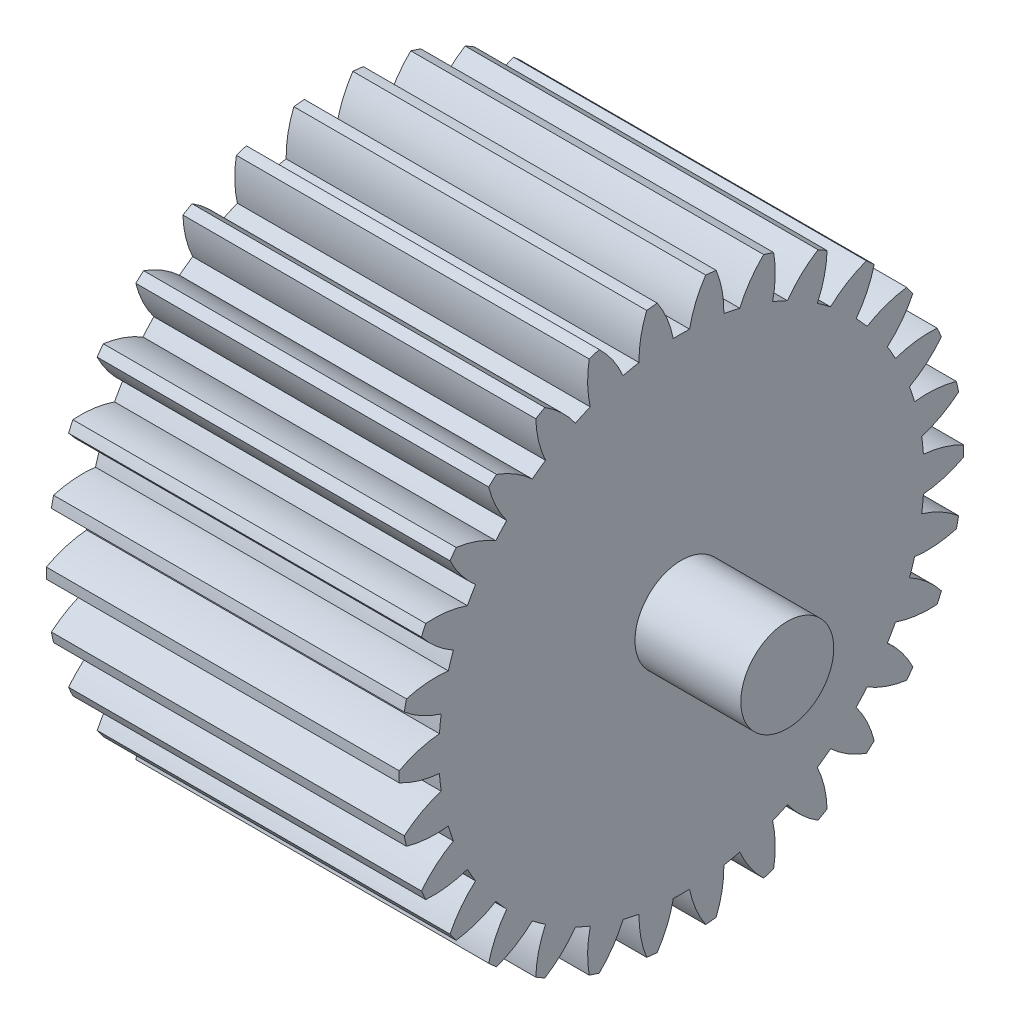
SolidWorks part; units mm, degrees
ref_plane "Plane1" through (0, 0, 0) normal (0, 0, 1) x (1, 0, 0)
ref_plane "Plane2" through (0, 0, 0) normal (0, 1, 0) x (1, 0, 0)
ref_plane "Plane3" through (0, 0, 0) normal (1, 0, 0) x (0, 0, -1)
sketch "HoldingSke" plane through (0, 0, 0) normal (0, 1, 0) x (1, 0, 0)
  line L0 (0, 0) -> (0.5774, -0.3333)
  line L1 (-15, 0) -> (100, 0) construction
  line L2 (0, 0) -> (-2.1039, 2.3779)
  line L3 (0, 0) -> (-11.863, 4.5341)
  line L4 (0, 0) -> (7.479, 4.318)
  line L5 (0, 0) -> (-37.4781, -13.9782)
  line L6 (0, 0) -> (-16.5793, -11.1861)
  line L7 (-2.1039, 2.3779) -> (6.5061, 41.4403)
  line L8 (-76.2, 54.61) -> (-74.8, 54.61)
  line L9 (-71.009, 38.7566) -> (-53.1078, 45.2721)
  line L10 (-76.2, 71.12) -> (104.1128, 71.12)
  line L11 (0, 0) -> (-20, 0)
  line L12 (-76.2, 101.6) -> (-76.147, 101.6)
  line L13 (24.9733, 27.94) -> (52.9518, 28.4284)
  line L14 (24.9733, 27.94) -> (24.9743, 27.94)
  line L15 (24.9733, 27.94) -> (100.4006, 29.5858)
  line L16 (-63.627, -1.5) -> (-12.827, -1.5)
  circle A0 centre (0, 0) radius 4
  circle A1 centre (0, 0) radius 10
  circle A2 centre (0, 0) radius 10
  circle A3 centre (0, 0) radius 4
  dimension "MHD" = 20
  dimension "Hub_dia" = 20
  dimension "Bore" = 8
  dimension "MBD" = 8
  dimension "Num_teeth" = 30
  dimension "Pitch" = 0.6667
  dimension "Overall_len" = 40
  dimension "Show_teeth" = 30
  dimension "Thickness" = 20
  dimension "OAL" = 40.0001
  dimension "T_dim" = 1.4
  dimension "Ap" = 20
  dimension "H" = 19.05
  dimension "Pitch_radius" = 180.3128
  dimension "Width" = 20
  dimension "Backlash" = 0.053
  dimension "Addendum_fac" = 1
  dimension "Dedendum_fac" = 1.25
  dimension "Clearance_fac" = 0.25
  dimension "Dedendum_add" = 0.001
  dimension "Module" = 1.5
sketch "BasProSke" plane through (0, 0, 0) normal (0, 1, 0) x (1, 0, 0)
  line L0 (-10, 0) -> (60, 0) construction
  line L1 (0, 0) -> (0, 24)
  line L2 (0, 0) -> (20, 0)
  line L3 (20, 0) -> (20, 24)
  line L4 (20, 24) -> (0, 24)
  dimension "Thickness" = 20
  dimension "Diameter" = 48
revolve "Base-Revolve" add sketch "BasProSke" angle 360 about L0
sketch "TooCutSke" plane through (0, 0, 0) normal (1, 0, 0) x (0, 0, -1)
  line L1 (0, 0) -> (0, 107) construction
  line L2 (0, 0) -> (-1.2703, 22.4641) construction
  line L3 (0, 0) -> (-4.6983, 44.7014) construction
  line L4 (-1.2703, 22.4641) -> (-2.3492, 22.3507) construction
  arc A0 (0.6933, 20.6123) -> (-0.6933, 20.6123) centre (0, 0) ccw
  arc A1 (2.0805, 23.9351) -> (-2.0805, 23.9351) centre (0, 0) ccw
  circle A2 centre (0, 0) radius 22.5 construction
  circle A3 centre (0, 0) radius 21.1431 construction
  arc A4 (-0.6933, 20.6123) -> (-2.0805, 23.9351) centre (-9.5243, 18.8764) ccw
  arc A5 (2.0805, 23.9351) -> (0.6933, 20.6123) centre (9.5243, 18.8764) ccw
  dimension "Root_dia" = 41.248
  dimension "Overcut_dia" = 48.0508
  dimension "Pitch_dia" = 45
  dimension "Base_dia" = 42.2862
  dimension "Flank_rad" = 9
  dimension "Half_ang" = 6
  dimension "Half_CT" = 1.0848
extrude "ToothCut" cut sketch "TooCutSke" along normal through all
fillet "Breaks" [suppressed] radius 0.03
fillet "RootFillets" [suppressed] radius 0.376
pattern_circular "TeethCuts" count 30 over 360 about axis through (0, 0, 0) along (1, 0, 0) of "ToothCut", "RootFillets", "Breaks"
sketch "HubNeaOneSke" plane through (0, 0, 0) normal (-1, 0, 0) x (0, 0, 1)
  circle A0 centre (0, 0) radius 10
  dimension "Diameter" = 20
extrude "HubNearOne" [suppressed] add sketch "HubNeaOneSke" along normal blind 20.0001
sketch "HubNeaBotSke" plane through (0, 0, 0) normal (-1, 0, 0) x (0, 0, 1)
  circle A0 centre (0, 0) radius 10
  dimension "Diameter" = 20
extrude "HubNearBoth" add sketch "HubNeaBotSke" along normal blind 10
ref_plane "FarPln" through (20, 0, 0) normal (1, 0, 0) x (0, 0, -1)
sketch "HubFarSke" plane through (20, 0, 0) normal (1, 0, 0) x (0, 0, -1)
  circle A0 centre (0, 0) radius 10
  dimension "Diameter" = 20
extrude "HubFar" add sketch "HubFarSke" along normal blind 10
sketch "BorSke" plane through (0, 0, 0) normal (1, 0, 0) x (0, 0, -1)
  circle A0 centre (0, 0) radius 4
  dimension "Diameter" = 8
extrude "Bore" cut sketch "BorSke" along normal mid plane 80.0001
sketch "KeySke" plane through (0, 0, 0) normal (1, 0, 0) x (0, 0, -1)
  line L0 (-1, 0) -> (-1, 5.4)
  line L1 (-1, 5.4) -> (1, 5.4)
  line L2 (1, 5.4) -> (1, 0)
  line L3 (0, 0) -> (0, 34) construction
  line L4 (-1, 0) -> (1, 0)
  dimension "Offset" = 5.4
extrude "Keyway" [suppressed] cut sketch "KeySke" along normal mid plane 80.0001
pattern_circular "Keyway2" [suppressed] count 2 every 90 about axis through (-10, 0, 0) along (1, 0, 0)
sketch "Croquis1" plane through (30, 0, 0) normal (1, 0, 0) x (0, 0, -1)
  circle A0 centre (0, 0) radius 10
extrude "Cortar-Extruir1" cut sketch "Croquis1" against normal up to surface (10 mm away) up to face at (20, 0, 10)
sketch "Croquis3" plane through (20, 0, 0) normal (1, 0, 0) x (0, 0, -1)
  circle A0 centre (0, 0) radius 4
extrude "Saliente-Extruir1" add sketch "Croquis3" against normal up to surface (30 mm away) up to face at (-10, 0, 4)
sketch "Croquis4" plane through (20, 0, 0) normal (1, 0, 0) x (0, 0, -1)
  circle A0 centre (0, 0) radius 3.95
  dimension "D1" = 7.9
extrude "Saliente-Extruir2" add sketch "Croquis4" along normal blind 9
sketch "Croquis5" plane through (-10, 0, 0) normal (-1, 0, 0) x (0, 0, 1)
  circle A0 centre (0, 0) radius 11.0881
extrude "Cortar-Extruir2" cut sketch "Croquis5" against normal up to surface (10 mm away) up to face at (0, 0, -10)
sketch "Croquis6" plane through (0, 0, 0) normal (-1, 0, 0) x (0, 0, 1)
  arc A120 (20.5719, -1.4651) -> (23.9958, -0.4465) centre (19.7685, 7.499) ccw
  arc A121 (23.9958, -0.4465) -> (23.9958, 0.4465) centre (0, 0) ccw
  arc A122 (23.9958, 0.4465) -> (20.5719, 1.4651) centre (19.7685, -7.499) ccw
  arc A123 (20.5719, 1.4651) -> (20.427, 2.8441) centre (0, 0) ccw
  arc A124 (20.427, 2.8441) -> (23.5643, 4.5523) centre (17.7774, 11.4452) ccw
  arc A125 (23.5643, 4.5523) -> (23.3787, 5.4257) centre (0, 0) ccw
  arc A126 (23.3787, 5.4257) -> (19.8177, 5.7102) centre (20.8957, -3.225) ccw
  arc A127 (19.8177, 5.7102) -> (19.3893, 7.0289) centre (0, 0) ccw
  arc A128 (19.3893, 7.0289) -> (22.1029, 9.3521) centre (15.0094, 14.8912) ccw
  arc A129 (22.1029, 9.3521) -> (21.7397, 10.1678) centre (0, 0) ccw
  arc A130 (21.7397, 10.1678) -> (18.1975, 9.7058) centre (21.1096, 1.1899) ccw
  arc A131 (18.1975, 9.7058) -> (17.5042, 10.9066) centre (0, 0) ccw
  arc A132 (17.5042, 10.9066) -> (19.6755, 13.7432) centre (11.5853, 17.6865) ccw
  arc A133 (19.6755, 13.7432) -> (19.1506, 14.4656) centre (0, 0) ccw
  arc A134 (19.1506, 14.4656) -> (15.7819, 13.2771) centre (20.4009, 5.5529) ccw
  arc A135 (15.7819, 13.2771) -> (14.8541, 14.3076) centre (0, 0) ccw
  arc A136 (14.8541, 14.3076) -> (16.3881, 17.5337) centre (7.6549, 19.7087) ccw
  arc A137 (16.3881, 17.5337) -> (15.7246, 18.1311) centre (0, 0) ccw
  arc A138 (15.7246, 18.1311) -> (12.6765, 16.2682) centre (18.8006, 9.6731) ccw
  arc A139 (12.6765, 16.2682) -> (11.5548, 17.0832) centre (0, 0) ccw
  arc A140 (11.5548, 17.0832) -> (12.3846, 20.5578) centre (3.39, 20.8696) ccw
  arc A141 (12.3846, 20.5578) -> (11.6113, 21.0042) centre (0, 0) ccw
  arc A142 (11.6113, 21.0042) -> (9.0171, 18.5483) centre (16.3786, 13.3706) ccw
  arc A143 (9.0171, 18.5483) -> (7.7505, 19.1123) centre (0, 0) ccw
  arc A144 (7.7505, 19.1123) -> (7.8397, 22.6834) centre (-1.0231, 21.1183) ccw
  arc A145 (7.8397, 22.6834) -> (6.9905, 22.9594) centre (0, 0) ccw
  arc A146 (6.9905, 22.9594) -> (4.9637, 20.0178) centre (13.2408, 16.4837) ccw
  arc A147 (4.9637, 20.0178) -> (3.6074, 20.3061) centre (0, 0) ccw
  arc A148 (3.6074, 20.3061) -> (2.9523, 23.8177) centre (-5.3915, 20.4441) ccw
  arc A149 (2.9523, 23.8177) -> (2.0642, 23.9111) centre (0, 0) ccw
  arc A150 (2.0642, 23.9111) -> (0.6933, 20.6123) centre (9.5243, 18.8764) ccw
  arc A151 (0.6933, 20.6123) -> (-0.6933, 20.6123) centre (0, 0) ccw
  arc A152 (-0.6933, 20.6123) -> (-2.0642, 23.9111) centre (-9.5243, 18.8764) ccw
  arc A153 (-2.0642, 23.9111) -> (-2.9523, 23.8177) centre (0, 0) ccw
  arc A154 (-2.9523, 23.8177) -> (-3.6074, 20.3061) centre (5.3915, 20.4441) ccw
  arc A155 (-3.6074, 20.3061) -> (-4.9637, 20.0178) centre (0, 0) ccw
  arc A156 (-4.9637, 20.0178) -> (-6.9905, 22.9594) centre (-13.2408, 16.4837) ccw
  arc A157 (-6.9905, 22.9594) -> (-7.8397, 22.6834) centre (0, 0) ccw
  arc A158 (-7.8397, 22.6834) -> (-7.7505, 19.1123) centre (1.0231, 21.1183) ccw
  arc A159 (-7.7505, 19.1123) -> (-9.0171, 18.5483) centre (0, 0) ccw
  arc A160 (-9.0171, 18.5483) -> (-11.6113, 21.0042) centre (-16.3786, 13.3706) ccw
  arc A161 (-11.6113, 21.0042) -> (-12.3846, 20.5578) centre (0, 0) ccw
  arc A162 (-12.3846, 20.5578) -> (-11.5548, 17.0832) centre (-3.39, 20.8696) ccw
  arc A163 (-11.5548, 17.0832) -> (-12.6765, 16.2682) centre (0, 0) ccw
  arc A164 (-12.6765, 16.2682) -> (-15.7246, 18.1311) centre (-18.8006, 9.6731) ccw
  arc A165 (-15.7246, 18.1311) -> (-16.3881, 17.5337) centre (0, 0) ccw
  arc A166 (-16.3881, 17.5337) -> (-14.8541, 14.3076) centre (-7.6549, 19.7087) ccw
  arc A167 (-14.8541, 14.3076) -> (-15.7819, 13.2771) centre (0, 0) ccw
  arc A168 (-15.7819, 13.2771) -> (-19.1506, 14.4656) centre (-20.4009, 5.5529) ccw
  arc A169 (-19.1506, 14.4656) -> (-19.6755, 13.7432) centre (0, 0) ccw
  arc A170 (-19.6755, 13.7432) -> (-17.5042, 10.9066) centre (-11.5853, 17.6865) ccw
  arc A171 (-17.5042, 10.9066) -> (-18.1975, 9.7058) centre (0, 0) ccw
  arc A172 (-18.1975, 9.7058) -> (-21.7397, 10.1678) centre (-21.1096, 1.1899) ccw
  arc A173 (-21.7397, 10.1678) -> (-22.1029, 9.3521) centre (0, 0) ccw
  arc A174 (-22.1029, 9.3521) -> (-19.3893, 7.0289) centre (-15.0094, 14.8912) ccw
  arc A175 (-19.3893, 7.0289) -> (-19.8177, 5.7102) centre (0, 0) ccw
  arc A176 (-19.8177, 5.7102) -> (-23.3787, 5.4257) centre (-20.8957, -3.225) ccw
  arc A177 (-23.3787, 5.4257) -> (-23.5643, 4.5523) centre (0, 0) ccw
  arc A178 (-23.5643, 4.5523) -> (-20.427, 2.8441) centre (-17.7774, 11.4452) ccw
  arc A179 (-20.427, 2.8441) -> (-20.5719, 1.4651) centre (0, 0) ccw
  arc A180 (-20.5719, 1.4651) -> (-23.9958, 0.4465) centre (-19.7685, -7.499) ccw
  arc A181 (-23.9958, 0.4465) -> (-23.9958, -0.4465) centre (0, 0) ccw
  arc A182 (-23.9958, -0.4465) -> (-20.5719, -1.4651) centre (-19.7685, 7.499) ccw
  arc A183 (-20.5719, -1.4651) -> (-20.427, -2.8441) centre (0, 0) ccw
  arc A184 (-20.427, -2.8441) -> (-23.5643, -4.5523) centre (-17.7774, -11.4452) ccw
  arc A185 (-23.5643, -4.5523) -> (-23.3787, -5.4257) centre (0, 0) ccw
  arc A186 (-23.3787, -5.4257) -> (-19.8177, -5.7102) centre (-20.8957, 3.225) ccw
  arc A187 (-19.8177, -5.7102) -> (-19.3893, -7.0289) centre (0, 0) ccw
  arc A188 (-19.3893, -7.0289) -> (-22.1029, -9.3521) centre (-15.0094, -14.8912) ccw
  arc A189 (-22.1029, -9.3521) -> (-21.7397, -10.1678) centre (0, 0) ccw
  arc A190 (-21.7397, -10.1678) -> (-18.1975, -9.7058) centre (-21.1096, -1.1899) ccw
  arc A191 (-18.1975, -9.7058) -> (-17.5042, -10.9066) centre (0, 0) ccw
  arc A192 (-17.5042, -10.9066) -> (-19.6755, -13.7432) centre (-11.5853, -17.6865) ccw
  arc A193 (-19.6755, -13.7432) -> (-19.1506, -14.4656) centre (0, 0) ccw
  arc A194 (-19.1506, -14.4656) -> (-15.7819, -13.2771) centre (-20.4009, -5.5529) ccw
  arc A195 (-15.7819, -13.2771) -> (-14.8541, -14.3076) centre (0, 0) ccw
  arc A196 (-14.8541, -14.3076) -> (-16.3881, -17.5337) centre (-7.6549, -19.7087) ccw
  arc A197 (-16.3881, -17.5337) -> (-15.7246, -18.1311) centre (0, 0) ccw
  arc A198 (-15.7246, -18.1311) -> (-12.6765, -16.2682) centre (-18.8006, -9.6731) ccw
  arc A199 (-12.6765, -16.2682) -> (-11.5548, -17.0832) centre (0, 0) ccw
  arc A200 (-11.5548, -17.0832) -> (-12.3846, -20.5578) centre (-3.39, -20.8696) ccw
  arc A201 (-12.3846, -20.5578) -> (-11.6113, -21.0042) centre (0, 0) ccw
  arc A202 (-11.6113, -21.0042) -> (-9.0171, -18.5483) centre (-16.3786, -13.3706) ccw
  arc A203 (-9.0171, -18.5483) -> (-7.7505, -19.1123) centre (0, 0) ccw
  arc A204 (-7.7505, -19.1123) -> (-7.8397, -22.6834) centre (1.0231, -21.1183) ccw
  arc A205 (-7.8397, -22.6834) -> (-6.9905, -22.9594) centre (0, 0) ccw
  arc A206 (-6.9905, -22.9594) -> (-4.9637, -20.0178) centre (-13.2408, -16.4837) ccw
  arc A207 (-4.9637, -20.0178) -> (-3.6074, -20.3061) centre (0, 0) ccw
  arc A208 (-3.6074, -20.3061) -> (-2.9523, -23.8177) centre (5.3915, -20.4441) ccw
  arc A209 (-2.9523, -23.8177) -> (-2.0642, -23.9111) centre (0, 0) ccw
  arc A210 (-2.0642, -23.9111) -> (-0.6933, -20.6123) centre (-9.5243, -18.8764) ccw
  arc A211 (-0.6933, -20.6123) -> (0.6933, -20.6123) centre (0, 0) ccw
  arc A212 (0.6933, -20.6123) -> (2.0642, -23.9111) centre (9.5243, -18.8764) ccw
  arc A213 (2.0642, -23.9111) -> (2.9523, -23.8177) centre (0, 0) ccw
  arc A214 (2.9523, -23.8177) -> (3.6074, -20.3061) centre (-5.3915, -20.4441) ccw
  arc A215 (3.6074, -20.3061) -> (4.9637, -20.0178) centre (0, 0) ccw
  arc A216 (4.9637, -20.0178) -> (6.9905, -22.9594) centre (13.2408, -16.4837) ccw
  arc A217 (6.9905, -22.9594) -> (7.8397, -22.6834) centre (0, 0) ccw
  arc A218 (7.8397, -22.6834) -> (7.7505, -19.1123) centre (-1.0231, -21.1183) ccw
  arc A219 (7.7505, -19.1123) -> (9.0171, -18.5483) centre (0, 0) ccw
  arc A220 (9.0171, -18.5483) -> (11.6113, -21.0042) centre (16.3786, -13.3706) ccw
  arc A221 (11.6113, -21.0042) -> (12.3846, -20.5578) centre (0, 0) ccw
  arc A222 (12.3846, -20.5578) -> (11.5548, -17.0832) centre (3.39, -20.8696) ccw
  arc A223 (11.5548, -17.0832) -> (12.6765, -16.2682) centre (0, 0) ccw
  arc A224 (12.6765, -16.2682) -> (15.7246, -18.1311) centre (18.8006, -9.6731) ccw
  arc A225 (15.7246, -18.1311) -> (16.3881, -17.5337) centre (0, 0) ccw
  arc A226 (16.3881, -17.5337) -> (14.8541, -14.3076) centre (7.6549, -19.7087) ccw
  arc A227 (14.8541, -14.3076) -> (15.7819, -13.2771) centre (0, 0) ccw
  arc A228 (15.7819, -13.2771) -> (19.1506, -14.4656) centre (20.4009, -5.5529) ccw
  arc A229 (19.1506, -14.4656) -> (19.6755, -13.7432) centre (0, 0) ccw
  arc A230 (19.6755, -13.7432) -> (17.5042, -10.9066) centre (11.5853, -17.6865) ccw
  arc A231 (17.5042, -10.9066) -> (18.1975, -9.7058) centre (0, 0) ccw
  arc A232 (18.1975, -9.7058) -> (21.7397, -10.1678) centre (21.1096, -1.1899) ccw
  arc A233 (21.7397, -10.1678) -> (22.1029, -9.3521) centre (0, 0) ccw
  arc A234 (22.1029, -9.3521) -> (19.3893, -7.0289) centre (15.0094, -14.8912) ccw
  arc A235 (19.3893, -7.0289) -> (19.8177, -5.7102) centre (0, 0) ccw
  arc A236 (19.8177, -5.7102) -> (23.3787, -5.4257) centre (20.8957, 3.225) ccw
  arc A237 (23.3787, -5.4257) -> (23.5643, -4.5523) centre (0, 0) ccw
  arc A238 (23.5643, -4.5523) -> (20.427, -2.8441) centre (17.7774, -11.4452) ccw
  arc A239 (20.427, -2.8441) -> (20.5719, -1.4651) centre (0, 0) ccw
  arc A240 (20.5719, -1.4651) -> (23.9958, -0.4465) centre (19.7685, 7.499) ccw
  arc A241 (23.9958, -0.4465) -> (23.9958, 0.4465) centre (0, 0) ccw
  arc A242 (23.9958, 0.4465) -> (20.5719, 1.4651) centre (19.7685, -7.499) ccw
  arc A243 (20.5719, 1.4651) -> (20.427, 2.8441) centre (0, 0) ccw
  arc A244 (20.427, 2.8441) -> (23.5643, 4.5523) centre (17.7774, 11.4452) ccw
  arc A245 (23.5643, 4.5523) -> (23.3787, 5.4257) centre (0, 0) ccw
  arc A246 (23.3787, 5.4257) -> (19.8177, 5.7102) centre (20.8957, -3.225) ccw
  arc A247 (19.8177, 5.7102) -> (19.3893, 7.0289) centre (0, 0) ccw
  arc A248 (19.3893, 7.0289) -> (22.1029, 9.3521) centre (15.0094, 14.8912) ccw
  arc A249 (22.1029, 9.3521) -> (21.7397, 10.1678) centre (0, 0) ccw
  arc A250 (21.7397, 10.1678) -> (18.1975, 9.7058) centre (21.1096, 1.1899) ccw
  arc A251 (18.1975, 9.7058) -> (17.5042, 10.9066) centre (0, 0) ccw
  arc A252 (17.5042, 10.9066) -> (19.6755, 13.7432) centre (11.5853, 17.6865) ccw
  arc A253 (19.6755, 13.7432) -> (19.1506, 14.4656) centre (0, 0) ccw
  arc A254 (19.1506, 14.4656) -> (15.7819, 13.2771) centre (20.4009, 5.5529) ccw
  arc A255 (15.7819, 13.2771) -> (14.8541, 14.3076) centre (0, 0) ccw
  arc A256 (14.8541, 14.3076) -> (16.3881, 17.5337) centre (7.6549, 19.7087) ccw
  arc A257 (16.3881, 17.5337) -> (15.7246, 18.1311) centre (0, 0) ccw
  arc A258 (15.7246, 18.1311) -> (12.6765, 16.2682) centre (18.8006, 9.6731) ccw
  arc A259 (12.6765, 16.2682) -> (11.5548, 17.0832) centre (0, 0) ccw
  arc A260 (11.5548, 17.0832) -> (12.3846, 20.5578) centre (3.39, 20.8696) ccw
  arc A261 (12.3846, 20.5578) -> (11.6113, 21.0042) centre (0, 0) ccw
  arc A262 (11.6113, 21.0042) -> (9.0171, 18.5483) centre (16.3786, 13.3706) ccw
  arc A263 (9.0171, 18.5483) -> (7.7505, 19.1123) centre (0, 0) ccw
  arc A264 (7.7505, 19.1123) -> (7.8397, 22.6834) centre (-1.0231, 21.1183) ccw
  arc A265 (7.8397, 22.6834) -> (6.9905, 22.9594) centre (0, 0) ccw
  arc A266 (6.9905, 22.9594) -> (4.9637, 20.0178) centre (13.2408, 16.4837) ccw
  arc A267 (4.9637, 20.0178) -> (3.6074, 20.3061) centre (0, 0) ccw
  arc A268 (3.6074, 20.3061) -> (2.9523, 23.8177) centre (-5.3915, 20.4441) ccw
  arc A269 (2.9523, 23.8177) -> (2.0642, 23.9111) centre (0, 0) ccw
  arc A270 (2.0642, 23.9111) -> (0.6933, 20.6123) centre (9.5243, 18.8764) ccw
  arc A271 (0.6933, 20.6123) -> (-0.6933, 20.6123) centre (0, 0) ccw
  arc A272 (-0.6933, 20.6123) -> (-2.0642, 23.9111) centre (-9.5243, 18.8764) ccw
  arc A273 (-2.0642, 23.9111) -> (-2.9523, 23.8177) centre (0, 0) ccw
  arc A274 (-2.9523, 23.8177) -> (-3.6074, 20.3061) centre (5.3915, 20.4441) ccw
  arc A275 (-3.6074, 20.3061) -> (-4.9637, 20.0178) centre (0, 0) ccw
  arc A276 (-4.9637, 20.0178) -> (-6.9905, 22.9594) centre (-13.2408, 16.4837) ccw
  arc A277 (-6.9905, 22.9594) -> (-7.8397, 22.6834) centre (0, 0) ccw
  arc A278 (-7.8397, 22.6834) -> (-7.7505, 19.1123) centre (1.0231, 21.1183) ccw
  arc A279 (-7.7505, 19.1123) -> (-9.0171, 18.5483) centre (0, 0) ccw
  arc A280 (-9.0171, 18.5483) -> (-11.6113, 21.0042) centre (-16.3786, 13.3706) ccw
  arc A281 (-11.6113, 21.0042) -> (-12.3846, 20.5578) centre (0, 0) ccw
  arc A282 (-12.3846, 20.5578) -> (-11.5548, 17.0832) centre (-3.39, 20.8696) ccw
  arc A283 (-11.5548, 17.0832) -> (-12.6765, 16.2682) centre (0, 0) ccw
  arc A284 (-12.6765, 16.2682) -> (-15.7246, 18.1311) centre (-18.8006, 9.6731) ccw
  arc A285 (-15.7246, 18.1311) -> (-16.3881, 17.5337) centre (0, 0) ccw
  arc A286 (-16.3881, 17.5337) -> (-14.8541, 14.3076) centre (-7.6549, 19.7087) ccw
  arc A287 (-14.8541, 14.3076) -> (-15.7819, 13.2771) centre (0, 0) ccw
  arc A288 (-15.7819, 13.2771) -> (-19.1506, 14.4656) centre (-20.4009, 5.5529) ccw
  arc A289 (-19.1506, 14.4656) -> (-19.6755, 13.7432) centre (0, 0) ccw
  arc A290 (-19.6755, 13.7432) -> (-17.5042, 10.9066) centre (-11.5853, 17.6865) ccw
  arc A291 (-17.5042, 10.9066) -> (-18.1975, 9.7058) centre (0, 0) ccw
  arc A292 (-18.1975, 9.7058) -> (-21.7397, 10.1678) centre (-21.1096, 1.1899) ccw
  arc A293 (-21.7397, 10.1678) -> (-22.1029, 9.3521) centre (0, 0) ccw
  arc A294 (-22.1029, 9.3521) -> (-19.3893, 7.0289) centre (-15.0094, 14.8912) ccw
  arc A295 (-19.3893, 7.0289) -> (-19.8177, 5.7102) centre (0, 0) ccw
  arc A296 (-19.8177, 5.7102) -> (-23.3787, 5.4257) centre (-20.8957, -3.225) ccw
  arc A297 (-23.3787, 5.4257) -> (-23.5643, 4.5523) centre (0, 0) ccw
  arc A298 (-23.5643, 4.5523) -> (-20.427, 2.8441) centre (-17.7774, 11.4452) ccw
  arc A299 (-20.427, 2.8441) -> (-20.5719, 1.4651) centre (0, 0) ccw
  arc A300 (-20.5719, 1.4651) -> (-23.9958, 0.4465) centre (-19.7685, -7.499) ccw
  arc A301 (-23.9958, 0.4465) -> (-23.9958, -0.4465) centre (0, 0) ccw
  arc A302 (-23.9958, -0.4465) -> (-20.5719, -1.4651) centre (-19.7685, 7.499) ccw
  arc A303 (-20.5719, -1.4651) -> (-20.427, -2.8441) centre (0, 0) ccw
  arc A304 (-20.427, -2.8441) -> (-23.5643, -4.5523) centre (-17.7774, -11.4452) ccw
  arc A305 (-23.5643, -4.5523) -> (-23.3787, -5.4257) centre (0, 0) ccw
  arc A306 (-23.3787, -5.4257) -> (-19.8177, -5.7102) centre (-20.8957, 3.225) ccw
  arc A307 (-19.8177, -5.7102) -> (-19.3893, -7.0289) centre (0, 0) ccw
  arc A308 (-19.3893, -7.0289) -> (-22.1029, -9.3521) centre (-15.0094, -14.8912) ccw
  arc A309 (-22.1029, -9.3521) -> (-21.7397, -10.1678) centre (0, 0) ccw
  arc A310 (-21.7397, -10.1678) -> (-18.1975, -9.7058) centre (-21.1096, -1.1899) ccw
  arc A311 (-18.1975, -9.7058) -> (-17.5042, -10.9066) centre (0, 0) ccw
  arc A312 (-17.5042, -10.9066) -> (-19.6755, -13.7432) centre (-11.5853, -17.6865) ccw
  arc A313 (-19.6755, -13.7432) -> (-19.1506, -14.4656) centre (0, 0) ccw
  arc A314 (-19.1506, -14.4656) -> (-15.7819, -13.2771) centre (-20.4009, -5.5529) ccw
  arc A315 (-15.7819, -13.2771) -> (-14.8541, -14.3076) centre (0, 0) ccw
  arc A316 (-14.8541, -14.3076) -> (-16.3881, -17.5337) centre (-7.6549, -19.7087) ccw
  arc A317 (-16.3881, -17.5337) -> (-15.7246, -18.1311) centre (0, 0) ccw
  arc A318 (-15.7246, -18.1311) -> (-12.6765, -16.2682) centre (-18.8006, -9.6731) ccw
  arc A319 (-12.6765, -16.2682) -> (-11.5548, -17.0832) centre (0, 0) ccw
  arc A320 (-11.5548, -17.0832) -> (-12.3846, -20.5578) centre (-3.39, -20.8696) ccw
  arc A321 (-12.3846, -20.5578) -> (-11.6113, -21.0042) centre (0, 0) ccw
  arc A322 (-11.6113, -21.0042) -> (-9.0171, -18.5483) centre (-16.3786, -13.3706) ccw
  arc A323 (-9.0171, -18.5483) -> (-7.7505, -19.1123) centre (0, 0) ccw
  arc A324 (-7.7505, -19.1123) -> (-7.8397, -22.6834) centre (1.0231, -21.1183) ccw
  arc A325 (-7.8397, -22.6834) -> (-6.9905, -22.9594) centre (0, 0) ccw
  arc A326 (-6.9905, -22.9594) -> (-4.9637, -20.0178) centre (-13.2408, -16.4837) ccw
  arc A327 (-4.9637, -20.0178) -> (-3.6074, -20.3061) centre (0, 0) ccw
  arc A328 (-3.6074, -20.3061) -> (-2.9523, -23.8177) centre (5.3915, -20.4441) ccw
  arc A329 (-2.9523, -23.8177) -> (-2.0642, -23.9111) centre (0, 0) ccw
  arc A330 (-2.0642, -23.9111) -> (-0.6933, -20.6123) centre (-9.5243, -18.8764) ccw
  arc A331 (-0.6933, -20.6123) -> (0.6933, -20.6123) centre (0, 0) ccw
  arc A332 (0.6933, -20.6123) -> (2.0642, -23.9111) centre (9.5243, -18.8764) ccw
  arc A333 (2.0642, -23.9111) -> (2.9523, -23.8177) centre (0, 0) ccw
  arc A334 (2.9523, -23.8177) -> (3.6074, -20.3061) centre (-5.3915, -20.4441) ccw
  arc A335 (3.6074, -20.3061) -> (4.9637, -20.0178) centre (0, 0) ccw
  arc A336 (4.9637, -20.0178) -> (6.9905, -22.9594) centre (13.2408, -16.4837) ccw
  arc A337 (6.9905, -22.9594) -> (7.8397, -22.6834) centre (0, 0) ccw
  arc A338 (7.8397, -22.6834) -> (7.7505, -19.1123) centre (-1.0231, -21.1183) ccw
  arc A339 (7.7505, -19.1123) -> (9.0171, -18.5483) centre (0, 0) ccw
  arc A340 (9.0171, -18.5483) -> (11.6113, -21.0042) centre (16.3786, -13.3706) ccw
  arc A341 (11.6113, -21.0042) -> (12.3846, -20.5578) centre (0, 0) ccw
  arc A342 (12.3846, -20.5578) -> (11.5548, -17.0832) centre (3.39, -20.8696) ccw
  arc A343 (11.5548, -17.0832) -> (12.6765, -16.2682) centre (0, 0) ccw
  arc A344 (12.6765, -16.2682) -> (15.7246, -18.1311) centre (18.8006, -9.6731) ccw
  arc A345 (15.7246, -18.1311) -> (16.3881, -17.5337) centre (0, 0) ccw
  arc A346 (16.3881, -17.5337) -> (14.8541, -14.3076) centre (7.6549, -19.7087) ccw
  arc A347 (14.8541, -14.3076) -> (15.7819, -13.2771) centre (0, 0) ccw
  arc A348 (15.7819, -13.2771) -> (19.1506, -14.4656) centre (20.4009, -5.5529) ccw
  arc A349 (19.1506, -14.4656) -> (19.6755, -13.7432) centre (0, 0) ccw
  arc A350 (19.6755, -13.7432) -> (17.5042, -10.9066) centre (11.5853, -17.6865) ccw
  arc A351 (17.5042, -10.9066) -> (18.1975, -9.7058) centre (0, 0) ccw
  arc A352 (18.1975, -9.7058) -> (21.7397, -10.1678) centre (21.1096, -1.1899) ccw
  arc A353 (21.7397, -10.1678) -> (22.1029, -9.3521) centre (0, 0) ccw
  arc A354 (22.1029, -9.3521) -> (19.3893, -7.0289) centre (15.0094, -14.8912) ccw
  arc A355 (19.3893, -7.0289) -> (19.8177, -5.7102) centre (0, 0) ccw
  arc A356 (19.8177, -5.7102) -> (23.3787, -5.4257) centre (20.8957, 3.225) ccw
  arc A357 (23.3787, -5.4257) -> (23.5643, -4.5523) centre (0, 0) ccw
  arc A358 (23.5643, -4.5523) -> (20.427, -2.8441) centre (17.7774, -11.4452) ccw
  arc A359 (20.427, -2.8441) -> (20.5719, -1.4651) centre (0, 0) ccw
  dimension "D1" = 0
extrude "Saliente-Extruir3" add sketch "Croquis6" along normal blind 10
sketch "Croquis7" plane through (-10, 0, 0) normal (-1, 0, 0) x (0, 0, 1)
  line L0 (0, 0) -> (0, 20.624) construction
  circle A0 centre (0, 0) radius 4
  arc A1 (0.6933, 20.6123) -> (-0.6933, 20.6123) centre (0, 0) ccw construction
  circle A2 centre (0, 10) radius 1.5
  circle A3 centre (10, 0) radius 1.5
  circle A4 centre (0, -10) radius 1.5
  circle A5 centre (-10, 0) radius 1.5
  point P18 (0, 0)
  dimension "D1" = 8
  dimension "D3" = 3
  dimension "D2" = 10
  dimension "D4" = 4
extrude "Cortar-Extruir3" cut sketch "Croquis7" against normal blind 10
equation "' \"Module@HoldingSke\" = 6.35"
equation "' \"Num_teeth@HoldingSke\" = 12"
equation "' \"Ap@HoldingSke\" =  20"
equation "' \"Ap@HoldingSke\" = 20"
equation "' \"Width@HoldingSke\" = 0.5 * 25.4"
equation "' \"Hub_dia@HoldingSke\"= 1 * 25.4"
equation "' \"Hub_dia@HoldingSke\" = 1 * 25.4"
equation "' \"Overall_len@HoldingSke\" = 1.0 * 25.4"
equation "' \"Bore@HoldingSke\" = 0.75 * 25.4"
equation "' \"T_dim@HoldingSke\" = 0.1 * 25.4"
equation "' \"Width@KeySke\" = 0.25 * 25.4"
equation "' \"Show_teeth@HoldingSke\" = 13"
equation "' \"Backlash@HoldingSke\" = 0.009 * 25.4"
equation "' \"Addendum_fac@HoldingSke\" = 1.0"
equation "' \"Dedendum_fac@HoldingSke\" = 1.25"
equation "' \"Dedendum_add@HoldingSke\" = 0.00005 * 25.4"
equation "' \"Clearance_fac@HoldingSke\" = 0.25"
equation "\"Pitch@HoldingSke\" = 1 / \"Module@HoldingSke\""
equation "\"Overcut_dia@TooCutSke\" = (\"Num_teeth@HoldingSke\" + 2 * \"Addendum_fac@HoldingSke\") / \"Pitch@HoldingSke\" + 0.002 * 25.4"
equation "\"Pitch_dia@TooCutSke\" = \"Num_teeth@HoldingSke\" / \"Pitch@HoldingSke\""
equation "\"Base_dia@TooCutSke\" = \"Num_teeth@HoldingSke\" / \"Pitch@HoldingSke\" * cos((\"Ap@HoldingSke\"  * 3.14159265 / 180))"
equation "\"Root_dia@TooCutSke\" = (\"Num_teeth@HoldingSke\" + 2) / \"Pitch@HoldingSke\" - 2 * (\"Addendum_fac@HoldingSke\" + \"Dedendum_fac@HoldingSke\") / \"Pitch@HoldingSke\" - \"Dedendum_add@HoldingSke\" * 2"
equation "\"Half_ang@TooCutSke\" = 180 / \"Num_teeth@HoldingSke\""
equation "\"Half_CT@TooCutSke\" = \"Num_teeth@HoldingSke\" / \"Pitch@HoldingSke\" * sin((3.14159265 / 2 / \"Num_teeth@HoldingSke\")) / 2 - 7 * \"Backlash@HoldingSke\" / 4"
equation "\"Flank_rad@TooCutSke\" = \"Num_teeth@HoldingSke\" / \"Pitch@HoldingSke\" / 5"
equation "\"Radius@RootFillets\" = \"Clearance_fac@HoldingSke\" / \"Pitch@HoldingSke\" + \"Dedendum_add@HoldingSke\""
equation "\"Break_rad@Breaks\" = 0.02 / \"Pitch@HoldingSke\""
equation "\"Thickness@HoldingSke\" = \"Width@HoldingSke\""
equation "\"OAL@HoldingSke\" = \"Thickness@HoldingSke\""
equation "\"MHD@HoldingSke\" = (\"Num_teeth@HoldingSke\" + 2) / \"Pitch@HoldingSke\" - 2 * (\"Addendum_fac@HoldingSke\" + \"Dedendum_fac@HoldingSke\")  / \"Pitch@HoldingSke\" - \"Dedendum_add@HoldingSke\" * 2"
equation "\"MBD@HoldingSke\" = (\"Num_teeth@HoldingSke\" + 2) / \"Pitch@HoldingSke\" - 2 * (\"Addendum_fac@HoldingSke\" + \"Dedendum_fac@HoldingSke\")  / \"Pitch@HoldingSke\" - \"Dedendum_add@HoldingSke\" * 2 - 0.002 * 25.4"
equation "\"MHD@HoldingSke\" = ((sgn( \"MHD@HoldingSke\" - \"Hub_dia@HoldingSke\" )-1)*( \"MHD@HoldingSke\" - \"Hub_dia@HoldingSke\" ))/-2+ \"Hub_dia@HoldingSke\""
equation "\"MBD@HoldingSke\" = ((sgn( \"MBD@HoldingSke\" - \"Bore@HoldingSke\" )-1)*( \"MBD@HoldingSke\" - \"Bore@HoldingSke\" ))/-2+ \"Bore@HoldingSke\""
equation "\"OAL@HoldingSke\" = ((sgn( \"OAL@HoldingSke\" - \"Overall_len@HoldingSke\" )+1)*( \"OAL@HoldingSke\" - \"Overall_len@HoldingSke\" ))/2 + \"Overall_len@HoldingSke\" + 0.000002 * 25.4"
equation "\"Num_teeth@TeethCuts\" = int( \"Show_teeth@HoldingSke\" ) + 1"
equation "\"Num_teeth@TeethCuts\" = ((sgn( \"Num_teeth@TeethCuts\" - \"Num_teeth@HoldingSke\" )-1)*( \"Num_teeth@TeethCuts\" - \"Num_teeth@HoldingSke\" ))/-2+ \"Num_teeth@HoldingSke\""
equation "\"Num_teeth@TeethCuts\" = ((sgn( \"Num_teeth@TeethCuts\" - 2.0)+1)*( \"Num_teeth@TeethCuts\" - 2.0))/2 +2.0"
equation "\"Angle@TeethCuts\" = 360.0 / \"Num_teeth@HoldingSke\""
equation "\"Diameter@BasProSke\" = (\"Num_teeth@HoldingSke\" + 2 * \"Addendum_fac@HoldingSke\") / \"Pitch@HoldingSke\""
equation "\"Thickness@BasProSke\"  = \"Thickness@HoldingSke\""
equation "' \"Fillet_rad@BasProSke\" =  \"Thickness@HoldingSke\" * 0.05"
equation "' \"Fillet_rad@BasProSke\" = \"Thickness@HoldingSke\" * 0.05"
equation "\"MHD@HoldingSke\" = ((sgn( \"MHD@HoldingSke\" - \"Root_dia@TooCutSke\" )-1)*( \"MHD@HoldingSke\" - \"Root_dia@TooCutSke\" ))/-2+ \"Root_dia@TooCutSke\""
equation "\"Diameter@HubNeaOneSke\" = \"MHD@HoldingSke\""
equation "\"Length@HubNearOne\" = \"OAL@HoldingSke\" - \"Thickness@BasProSke\""
equation "\"Diameter@HubNeaBotSke\" = \"MHD@HoldingSke\""
equation "\"Length@HubNearBoth\" = ( \"OAL@HoldingSke\" - \"Thickness@BasProSke\" ) / 2.0"
equation "\"Thickness@FarPln\" = \"Thickness@BasProSke\""
equation "\"Diameter@HubFarSke\" = \"MHD@HoldingSke\""
equation "\"Length@HubFar\" = ( \"OAL@HoldingSke\" - \"Thickness@BasProSke\" ) / 2.0"
equation "\"Diameter@BorSke\" = \"MBD@HoldingSke\""
equation "\"D1@Bore\" = \"OAL@HoldingSke\" * 2.0"
equation "\"D1@Keyway\" = \"OAL@HoldingSke\" * 2.0"
equation "\"Offset@KeySke\" = \"T_dim@HoldingSke\" + \"MBD@HoldingSke\" / 2.0"
